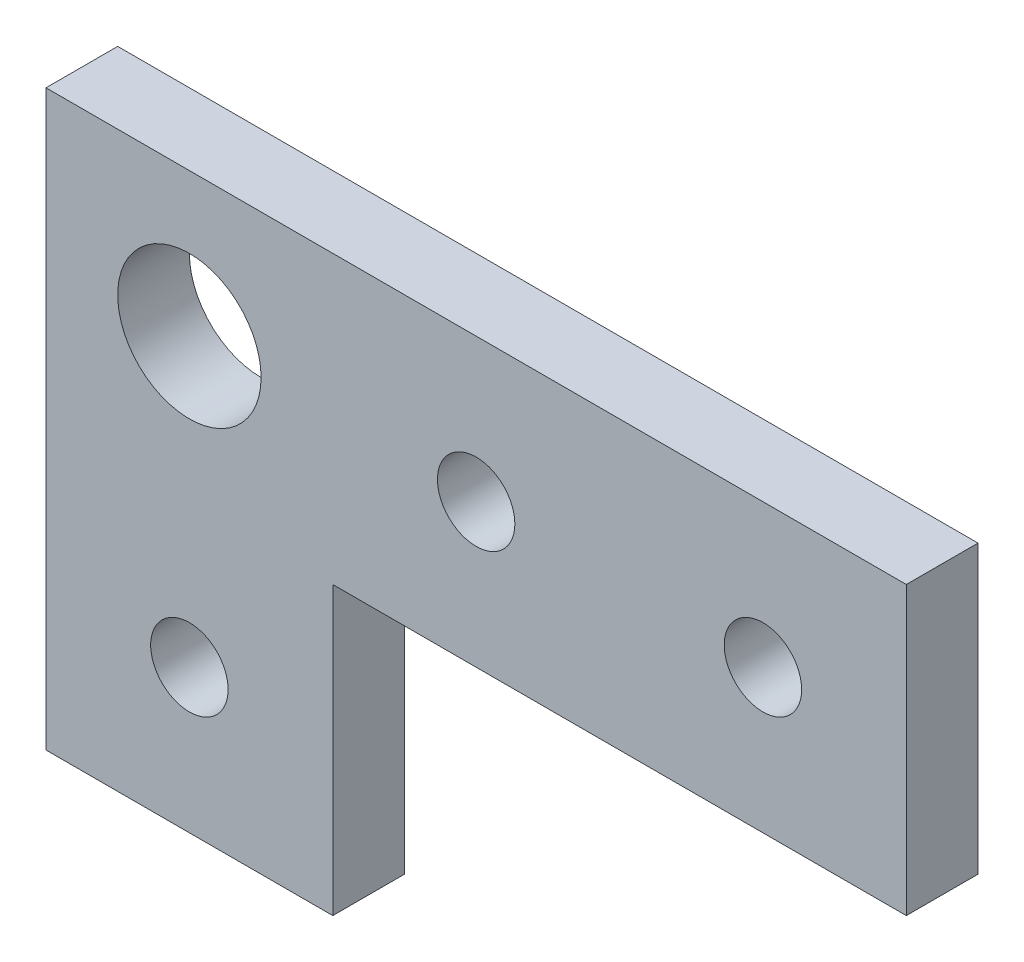
SolidWorks part; units mm, degrees
ref_plane "Front Plane" through (0, 0, 0) normal (0, 0, 1) x (1, 0, 0)
ref_plane "Top Plane" through (0, 0, 0) normal (0, 1, 0) x (1, 0, 0)
ref_plane "Right Plane" through (0, 0, 0) normal (1, 0, 0) x (0, 0, -1)
sketch "Sketch1" plane through (0, 0, 0) normal (0, 0, 1) x (1, 0, 0)
  line L0 (0, 0) -> (0, 50.8)
  line L1 (0, 50.8) -> (76.2, 50.8)
  line L2 (76.2, 50.8) -> (76.2, 25.4)
  line L3 (76.2, 25.4) -> (25.4, 25.4)
  line L4 (25.4, 25.4) -> (25.4, 0)
  line L5 (25.4, 0) -> (0, 0)
  dimension "D1" = 25.4
  dimension "D2" = 50.8
  dimension "D3" = 76.2
extrude "Boss-Extrude1" add sketch "Sketch1" along normal blind 6.35
sketch "Sketch2" plane through (0, 0, 6.35) normal (0, 0, 1) x (1, 0, 0)
  line L0 (12.7, 0) -> (12.7, 59.278) construction
  line L1 (0, 0) -> (25.4, 0) construction
  line L2 (76.2, 38.1) -> (-9.229, 38.1) construction
  line L3 (76.2, 25.4) -> (76.2, 50.8) construction
  circle A0 centre (12.7, 38.1) radius 6.35
  circle A1 centre (12.7, 12.7) radius 3.429
  circle A2 centre (38.1, 38.1) radius 3.429
  circle A3 centre (63.5, 38.1) radius 3.429
  dimension "D1" = 6.858
  dimension "D3" = 25.4
  dimension "D5" = 12.7
  dimension "D2" = 12.7
  dimension "D4" = 25.4
extrude "Cut-Extrude1" cut sketch "Sketch2" against normal up to surface (6.35 mm away) up to face at (33.8667, 25.4, 0)
